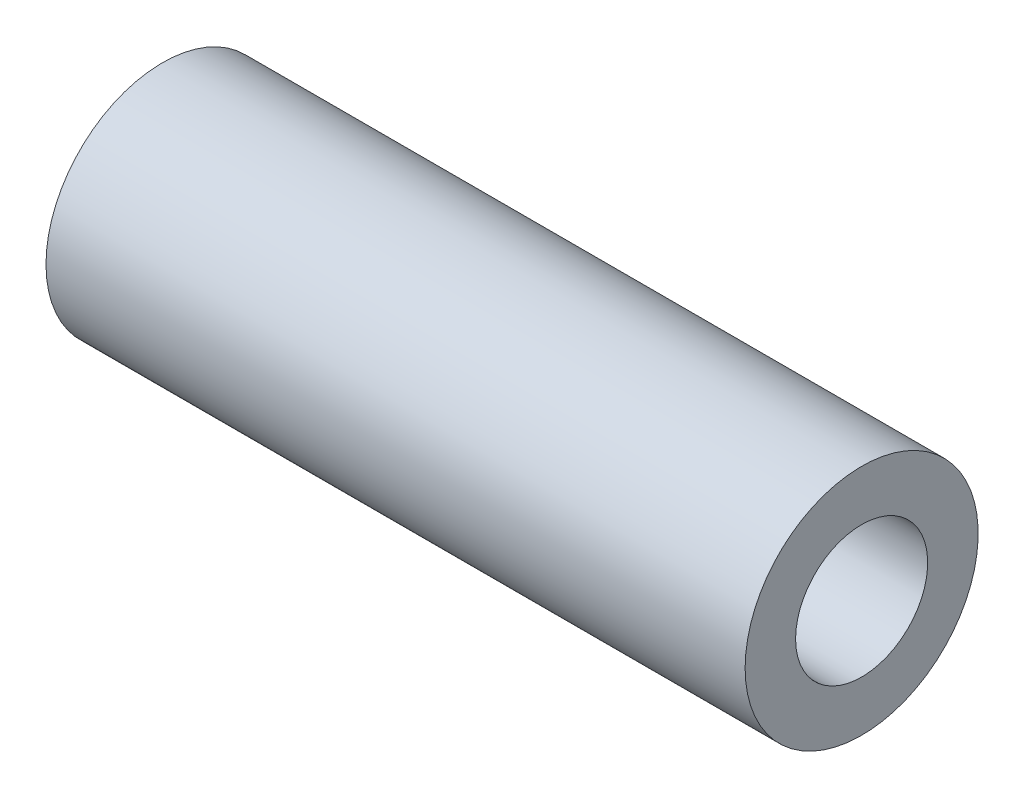
SolidWorks part; units mm, degrees
ref_plane "Front Plane" through (0, 0, 0) normal (0, 0, 1) x (1, 0, 0)
ref_plane "Top Plane" through (0, 0, 0) normal (0, 1, 0) x (1, 0, 0)
ref_plane "Right Plane" through (0, 0, 0) normal (1, 0, 0) x (0, 0, -1)
sketch "Sketch1" plane through (0, 0, 0) normal (1, 0, 0) x (0, 0, -1)
  circle A0 centre (0, 0) radius 1.8
  circle A1 centre (0, 0) radius 3.175
  dimension "D1" = 3.6
  dimension "D2" = 6.35
extrude "Boss-Extrude1" add sketch "Sketch1" along normal blind 19.05
